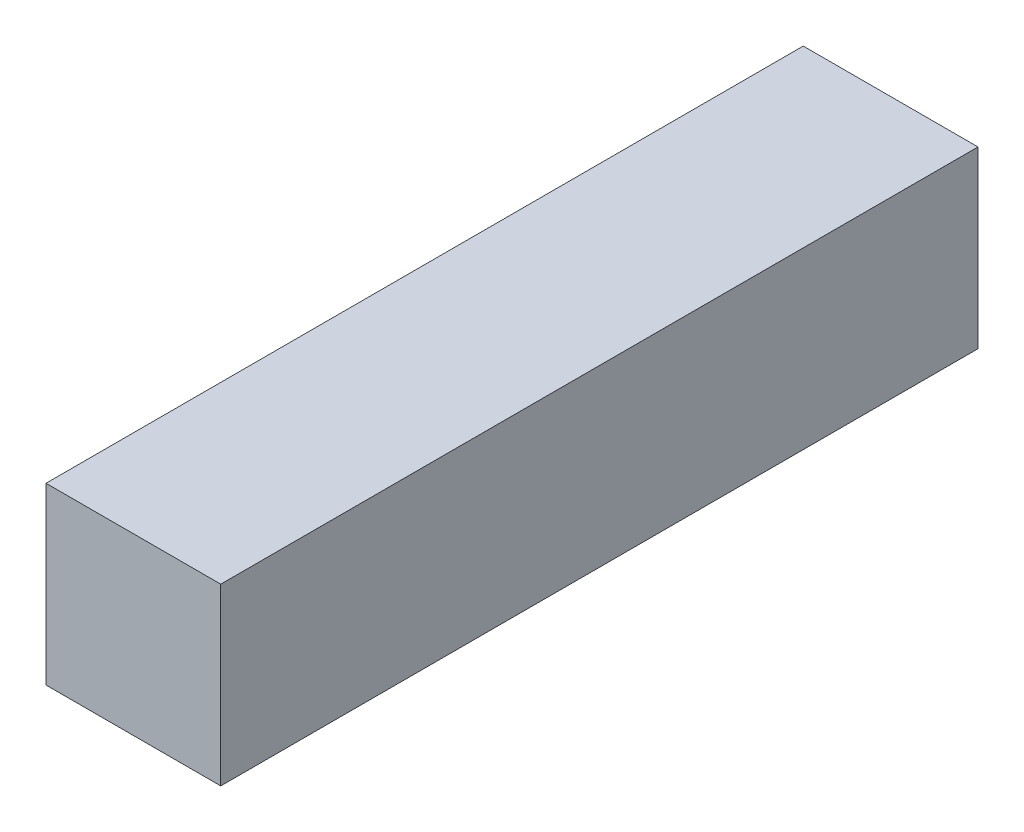
SolidWorks part; units mm, degrees
ref_plane "Front Plane" through (0, 0, 0) normal (0, 0, 1) x (1, 0, 0)
ref_plane "Top Plane" through (0, 0, 0) normal (0, 1, 0) x (1, 0, 0)
ref_plane "Right Plane" through (0, 0, 0) normal (1, 0, 0) x (0, 0, -1)
sketch "Sketch1" plane through (0, 0, 0) normal (0, 0, 1) x (1, 0, 0)
  line L1 (-15, 15) -> (15, 15)
  line L2 (-15, 15) -> (-15, -15)
  line L3 (-15, -15) -> (15, -15)
  line L4 (15, 15) -> (15, -15)
  line L5 (-15, 15) -> (15, -15) construction
  line L6 (-15, -15) -> (15, 15) construction
  point P0 (0, 0)
  dimension "D1" = 30
extrude "Boss-Extrude1" add sketch "Sketch1" along normal mid plane 130
